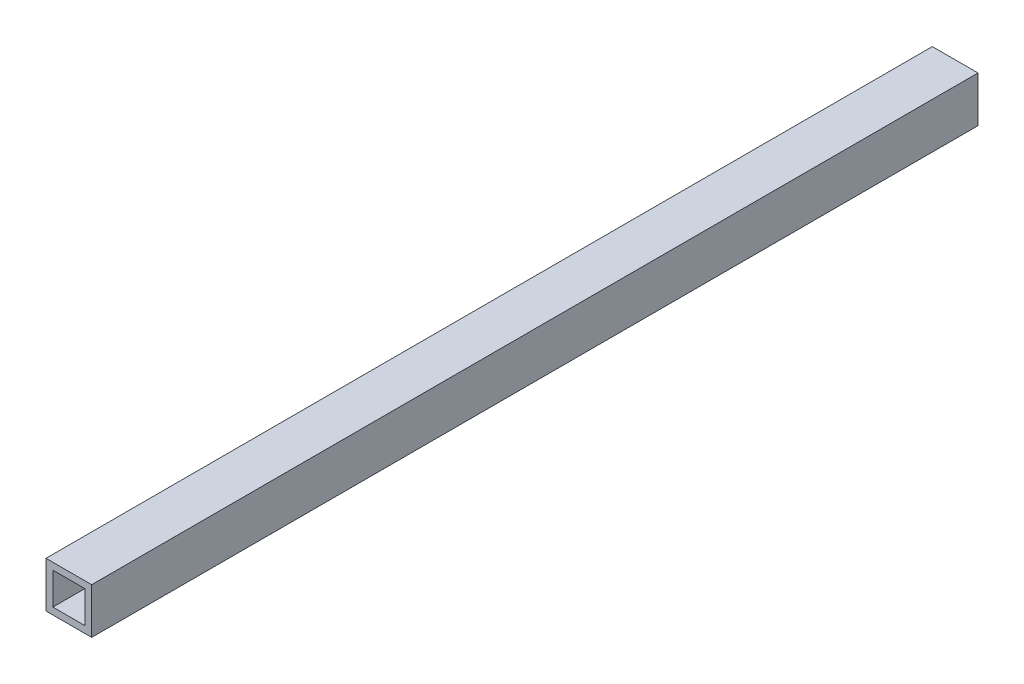
SolidWorks part; units mm, degrees
ref_plane "Front Plane" through (0, 0, 0) normal (0, 0, 1) x (1, 0, 0)
ref_plane "Top Plane" through (0, 0, 0) normal (0, 1, 0) x (1, 0, 0)
ref_plane "Right Plane" through (0, 0, 0) normal (1, 0, 0) x (0, 0, -1)
sketch "Sketch1" plane through (0, 0, 0) normal (0, 0, 1) x (1, 0, 0)
  line L1 (-5, 5) -> (5, 5)
  line L2 (-5, 5) -> (-5, -5)
  line L3 (-5, -5) -> (5, -5)
  line L4 (5, 5) -> (5, -5)
  line L5 (-5, 5) -> (5, -5) construction
  line L6 (-5, -5) -> (5, 5) construction
  line L7 (-3.5, -3.5) -> (3.5, -3.5)
  line L8 (-3.5, -3.5) -> (-3.5, 3.5)
  line L9 (-3.5, 3.5) -> (3.5, 3.5)
  line L10 (3.5, -3.5) -> (3.5, 3.5)
  line L11 (-3.5, -3.5) -> (3.5, 3.5) construction
  line L12 (-3.5, 3.5) -> (3.5, -3.5) construction
  point P0 (0, 0)
  point P6 (0, 0)
  dimension "D1" = 10
  dimension "D2" = 10
  dimension "D3" = 1.5
extrude "Boss-Extrude1" add sketch "Sketch1" along normal blind 194
